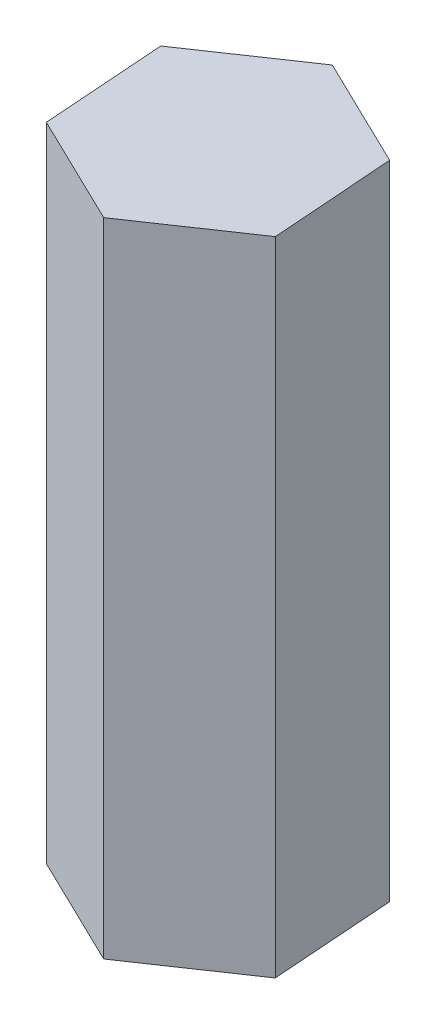
SolidWorks part; units mm, degrees
ref_plane "Front" through (0, 0, 0) normal (0, 0, 1) x (1, 0, 0)
ref_plane "Top" through (0, 0, 0) normal (0, 1, 0) x (1, 0, 0)
ref_plane "Right" through (0, 0, 0) normal (1, 0, 0) x (0, 0, -1)
sketch "Sketch2" plane through (0, 0, 0) normal (0, 1, 0) x (1, 0, 0)
  line L1 (2.598, -1.2584) -> (2.3888, 1.6207)
  line L2 (2.3888, 1.6207) -> (-0.2092, 2.8792)
  line L3 (-0.2092, 2.8792) -> (-2.598, 1.2584)
  line L4 (-2.598, 1.2584) -> (-2.3888, -1.6207)
  line L5 (-2.3888, -1.6207) -> (0.2092, -2.8792)
  line L6 (0.2092, -2.8792) -> (2.598, -1.2584)
  circle A0 centre (0, 0) radius 2.5 construction
  dimension "D1" = 2.5
extrude "Boss-Extrude1" add sketch "Sketch2" along normal blind 15
